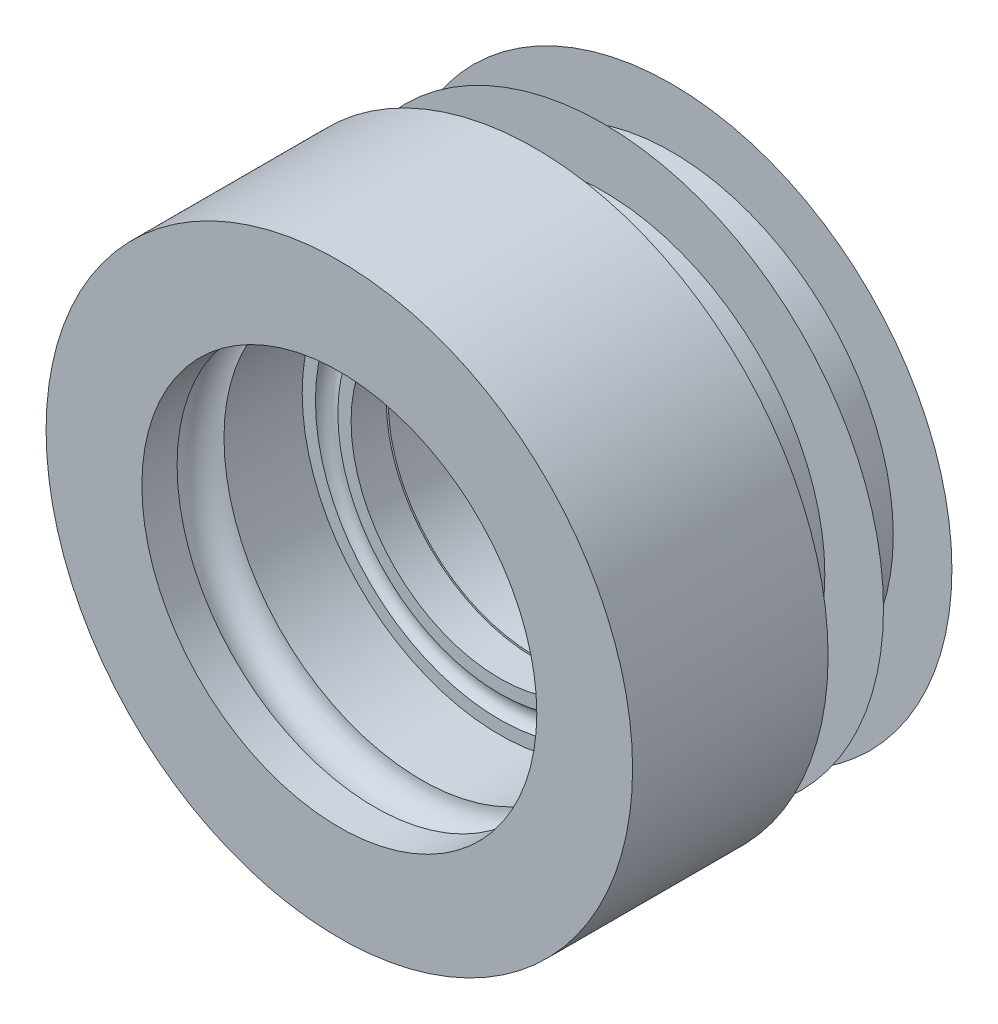
SolidWorks part; units mm, degrees
ref_plane "Front Plane" through (0, 0, 0) normal (0, 0, 1) x (1, 0, 0)
ref_plane "Top Plane" through (0, 0, 0) normal (0, 1, 0) x (1, 0, 0)
ref_plane "Right Plane" through (0, 0, 0) normal (1, 0, 0) x (0, 0, -1)
sketch "Sketch1" plane through (0, 0, 0) normal (0, 0, 1) x (1, 0, 0)
  circle A0 centre (0, 0) radius 15
  dimension "D1" = 30
extrude "Boss-Extrude1" add sketch "Sketch1" along normal blind 10
sketch "Sketch2" plane through (0, 0, 10) normal (0, 0, 1) x (1, 0, 0)
  circle A0 centre (0, 0) radius 10.1
  circle A1 centre (0, 0) radius 15 construction
  dimension "D1" = 4.9
extrude "Cut-Extrude1" cut sketch "Sketch2" against normal through all
sketch "Sketch4" plane through (0, 0, 0) normal (1, 0, 0) x (0, 0, -1)
  line L0 (0, 0) -> (-10, 0) construction
  line L1 (-10, 15) -> (-10, -15) construction
sketch "Sketch3" plane through (0, 0, 0) normal (1, 0, 0) x (0, 0, -1)
  line L0 (-10, 10.1) -> (-10, -10.1) construction
  circle A0 centre (-7, 10.1) radius 1.2
  dimension "D1" = 2.4
  dimension "D2" = 3
  dimension "D3" = 0
revolve "Cut-Revolve2" cut sketch "Sketch3" angle 360 about L0
sketch "Sketch5" plane through (0, 0, 0) normal (1, 0, 0) x (0, 0, -1)
  line L1 (-1.8, -7.6) -> (9.2, -7.6)
  line L2 (-1.8, -7.6) -> (-1.8, -11.1)
  line L3 (-1.8, -11.1) -> (9.2, -11.1)
  line L4 (9.2, -7.6) -> (9.2, -11.1)
  dimension "D1" = 1
  dimension "D2" = 3.5
  dimension "D3" = 11
  dimension "D4" = 4
revolve "Revolve1" add sketch "Sketch5" angle 360 about L0
sketch "Sketch7" plane through (0, 0, 0) normal (1, 0, 0) x (0, 0, -1)
  circle A0 centre (-2.05, 8.85) radius 0.625
  dimension "D1" = 1.25
  dimension "D2" = 1.25
  dimension "D3" = 0.25
revolve "Cut-Revolve3" cut sketch "Sketch7" angle 360 about L0
sketch "Sketch9" plane through (0, 0, 0) normal (0, 0, -1) x (-1, 0, 0)
  circle A0 centre (0, 0) radius 11.3327
extrude "Boss-Extrude2" add sketch "Sketch9" along normal blind 9
sketch "Sketch10" plane through (0, 0, -9) normal (0, 0, -1) x (-1, 0, 0)
  circle A0 centre (0, 0) radius 7.5
  dimension "D1" = 15
extrude "Cut-Extrude2" cut sketch "Sketch10" against normal through all
sketch "Sketch11" plane through (0, 0, 0) normal (1, 0, 0) x (0, 0, -1)
  line L0 (9, 11.3327) -> (7, 11.3327)
  line L1 (9, 11.3327) -> (0, 11.3327) construction
  line L2 (7, 11.3327) -> (7, 14.3327)
  line L3 (7, 14.3327) -> (9, 11.3327)
  dimension "D1" = 2
  dimension "D2" = 3
revolve "Revolve2" add sketch "Sketch11" angle 360 about L0
pattern_linear "LPattern1" count 3 spacing 3.5 along (0, 0, 1) of "Revolve2"
